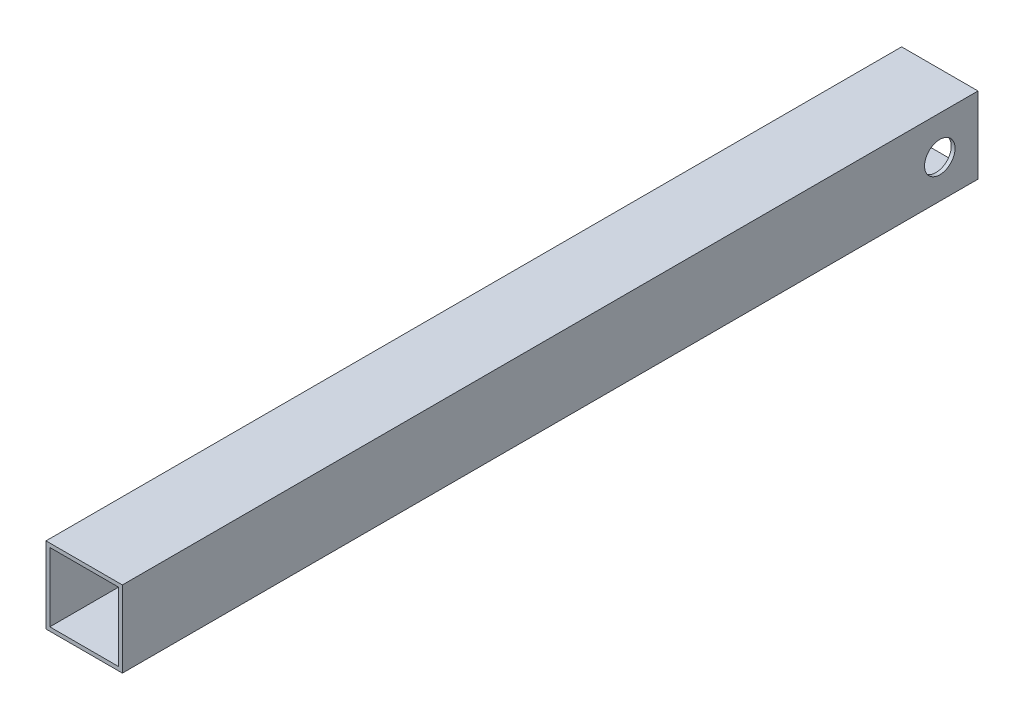
SolidWorks part; units mm, degrees
material "6061 Alloy"
ref_plane "Front Plane" through (0, 0, 0) normal (0, 0, 1) x (1, 0, 0)
ref_plane "Top Plane" through (0, 0, 0) normal (0, 1, 0) x (1, 0, 0)
ref_plane "Right Plane" through (0, 0, 0) normal (1, 0, 0) x (0, 0, -1)
sketch "Sketch1" plane through (0, 0, 0) normal (0, 0, 1) x (1, 0, 0)
  line L1 (-28.575, -28.575) -> (28.575, -28.575)
  line L2 (-28.575, -28.575) -> (-28.575, 28.575)
  line L3 (-28.575, 28.575) -> (28.575, 28.575)
  line L4 (28.575, -28.575) -> (28.575, 28.575)
  line L5 (-28.575, -28.575) -> (28.575, 28.575) construction
  line L6 (-28.575, 28.575) -> (28.575, -28.575) construction
  line L7 (-31.75, -31.75) -> (31.75, -31.75)
  line L8 (-31.75, -31.75) -> (-31.75, 31.75)
  line L9 (-31.75, 31.75) -> (31.75, 31.75)
  line L10 (31.75, -31.75) -> (31.75, 31.75)
  line L11 (-31.75, -31.75) -> (31.75, 31.75) construction
  line L12 (-31.75, 31.75) -> (31.75, -31.75) construction
  point P0 (0, 0)
  point P6 (0, 0)
  dimension "D1" = 3.175
  dimension "D2" = 63.5
extrude "Boss-Extrude1" add sketch "Sketch1" along normal mid plane 711.2
sketch "Sketch2" plane through (-31.75, 0, 0) normal (-1, 0, 0) x (0, 0, 1)
  line L0 (-355.6, 31.75) -> (-323.85, 0) construction
  line L1 (-323.85, 0) -> (-355.6, -31.75) construction
  circle A0 centre (-323.85, 0) radius 12.7
  dimension "D1" = 25.4
extrude "Cut-Extrude1" cut sketch "Sketch2" against normal through all
